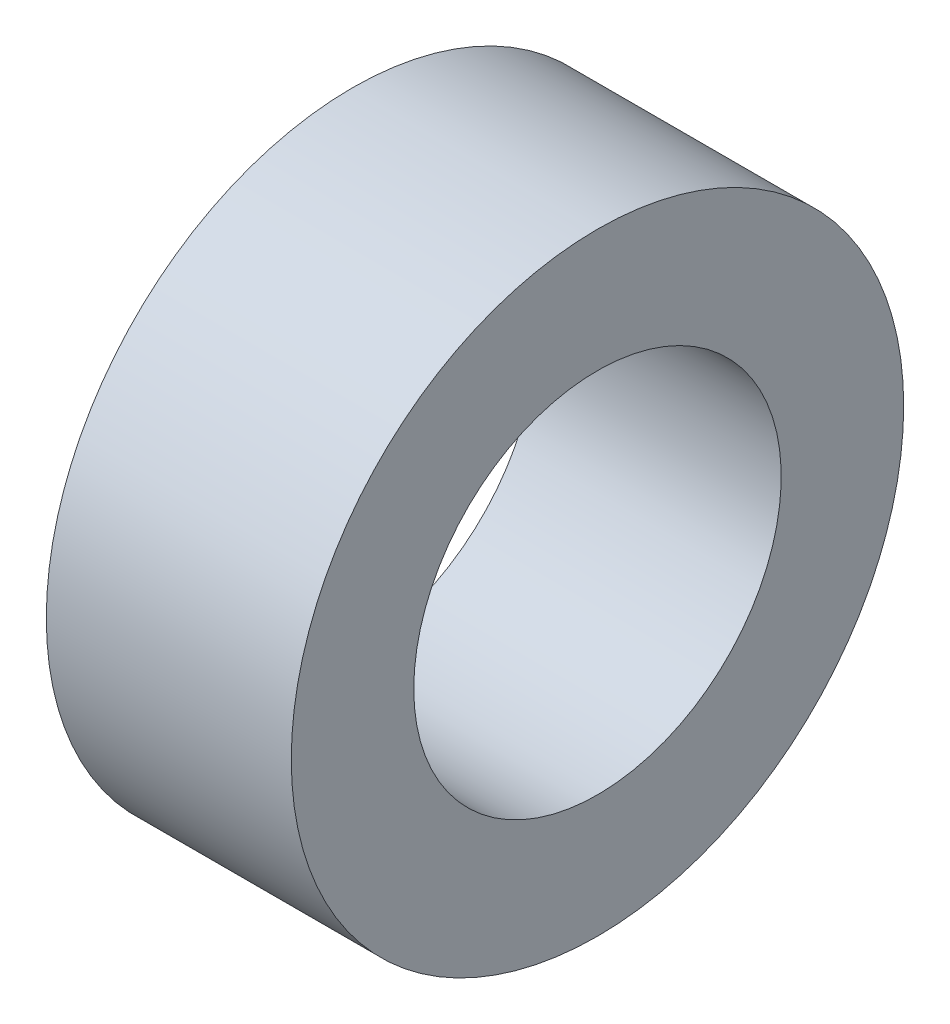
SolidWorks part; units mm, degrees
ref_plane "Front Plane" through (0, 0, 0) normal (0, 0, 1) x (1, 0, 0)
ref_plane "Top Plane" through (0, 0, 0) normal (0, 1, 0) x (1, 0, 0)
ref_plane "Right Plane" through (0, 0, 0) normal (1, 0, 0) x (0, 0, -1)
sketch "Sketch1" plane through (0, 0, 0) normal (0, 0, 1) x (1, 0, 0)
  line L0 (0, 0) -> (0.8349, 0) construction
  line L1 (1, 1.5) -> (-1, 1.5)
  line L2 (1, 1.5) -> (1, 2.5)
  line L3 (1, 2.5) -> (-1, 2.5)
  line L4 (-1, 1.5) -> (-1, 2.5)
  line L5 (1, 1.5) -> (-1, 2.5) construction
  line L6 (1, 2.5) -> (-1, 1.5) construction
  point P0 (0, 2)
  point P8 (0, 0)
  dimension "D1" = 1.5
  dimension "D2" = 2.5
  dimension "D3" = 2
revolve "Revolve1" add sketch "Sketch1" angle 360 about L0
